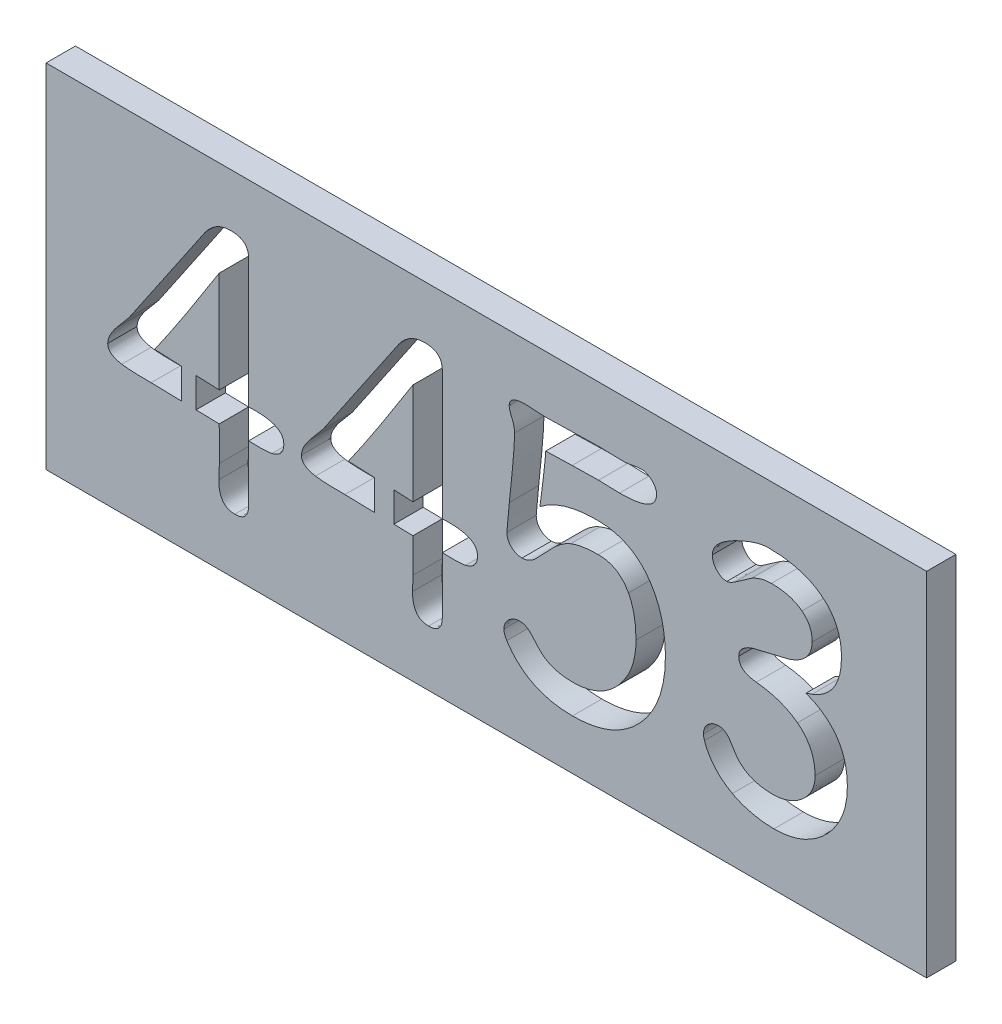
SolidWorks part; units mm, degrees
ref_plane "Front" through (0, 0, 0) normal (0, 0, 1) x (1, 0, 0)
ref_plane "Top" through (0, 0, 0) normal (0, 1, 0) x (1, 0, 0)
ref_plane "Right" through (0, 0, 0) normal (1, 0, 0) x (0, 0, -1)
sketch "Sketch1" plane through (0, 0, 0) normal (0, 0, 1) x (1, 0, 0)
  line L1 (-190.5, -76.2) -> (190.5, -76.2)
  line L2 (-190.5, -76.2) -> (-190.5, 76.2)
  line L3 (-190.5, 76.2) -> (190.5, 76.2)
  line L4 (190.5, -76.2) -> (190.5, 76.2)
  line L5 (-190.5, -76.2) -> (190.5, 76.2) construction
  line L6 (-190.5, 76.2) -> (190.5, -76.2) construction
  point P0 (0, 0)
  dimension "D1" = 152.4
  dimension "D2" = 381
extrude "Boss-Extrude1" add sketch "Sketch1" along normal blind 12.7
sketch "Sketch2" plane through (0, 0, 12.7) normal (0, 0, 1) x (1, 0, 0)
  line L0 (-190.5, -50.8) -> (190.5, -50.8) construction
  line L1 (-190.5, 76.2) -> (-190.5, -76.2) construction
  line L2 (190.5, -76.2) -> (190.5, 76.2) construction
  line L3 (-190.5, -50.8) -> (-190.5, -76.2) construction
  line L4 (-190.5, -50.8) -> (-190.5, 50.8) construction
  line L5 (-190.5, 50.8) -> (-190.5, 76.2) construction
  text T0 "4453" font "Comic Sans MS" height 101.6
  dimension "D1" = 101.6
extrude "Cut-Extrude1" cut sketch "Sketch2" against normal through all
sketch "Sketch3" plane through (0, 0, 12.7) normal (0, 0, 1) x (1, 0, 0)
  line L1 (-131.8626, -2.7967) -> (-125.6142, -2.7967)
  line L2 (-131.8626, -2.7967) -> (-131.8626, -29.0398)
  line L3 (-131.8626, -29.0398) -> (-125.6142, -29.0398)
  line L4 (-125.6142, -2.7967) -> (-125.6142, -29.0398)
  line L5 (-48.3428, -5.0877) -> (-40.0117, -5.0877)
  line L6 (-48.3428, -5.0877) -> (-48.3428, -29.0398)
  line L7 (-48.3428, -29.0398) -> (-40.0117, -29.0398)
  line L8 (-40.0117, -5.0877) -> (-40.0117, -29.0398)
extrude "Boss-Extrude2" add sketch "Sketch3" against normal up to surface (12.7 mm away) up to face at (-120.2267, 13.2292, 0)
